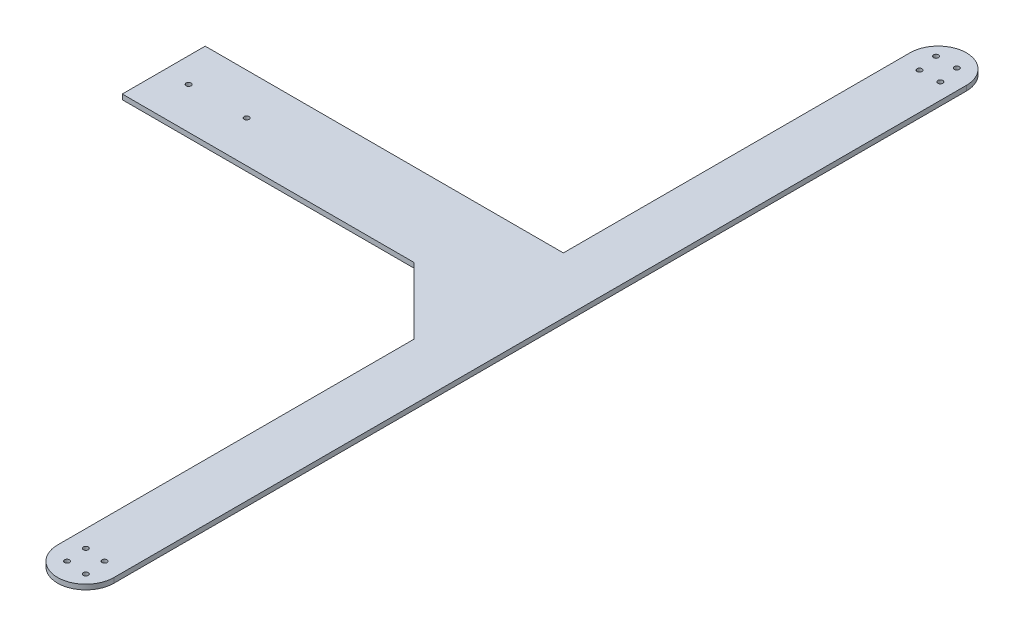
SolidWorks part; units mm, degrees
ref_plane "Front Plane" through (0, 0, 0) normal (0, 0, 1) x (1, 0, 0)
ref_plane "Top Plane" through (0, 0, 0) normal (0, 1, 0) x (1, 0, 0)
ref_plane "Right Plane" through (0, 0, 0) normal (1, 0, 0) x (0, 0, -1)
sketch "Sketch1" plane through (0, 0, 0) normal (0, 1, 0) x (1, 0, 0)
  line L0 (0, 0) -> (176, 0)
  line L1 (216, -40) -> (216, -255)
  line L2 (0, 0) -> (0, 50)
  line L3 (0, 50) -> (216, 50)
  line L4 (216, 50) -> (216, 259.0603)
  line L5 (250, -255) -> (250, 259.0603)
  line L6 (50, -120) -> (250, -120) construction
  line L7 (50, 150) -> (50, -120) construction
  line L8 (50, 150) -> (250, 120) construction
  line L9 (176, 0) -> (216, -40)
  line L10 (227.9078, 252.8902) -> (238.0922, 265.2304) construction
  line L11 (240.327, 253.0134) -> (225.673, 265.1073) construction
  line L12 (227.3431, -260.6569) -> (238.6569, -249.3431) construction
  line L13 (0, 25) -> (250, 25) construction
  line L14 (226.2825, -248.2825) -> (239.7175, -261.7175) construction
  arc A0 (216, -255) -> (250, -255) centre (233, -255) ccw
  arc A1 (216, 259.0603) -> (250, 259.0603) centre (233, 259.0603) cw
  circle A2 centre (233, -255) radius 135 construction
  circle A3 centre (233, 259.0603) radius 135 construction
  circle A4 centre (238.0922, 265.2304) radius 1.5
  circle A5 centre (225.673, 265.1073) radius 1.5
  circle A6 centre (227.9078, 252.8902) radius 1.5
  circle A7 centre (240.327, 253.0134) radius 1.5
  circle A8 centre (226.2825, -248.2825) radius 1.5
  circle A9 centre (238.6569, -249.3431) radius 1.5
  circle A10 centre (239.7175, -261.7175) radius 1.5
  circle A11 centre (227.3431, -260.6569) radius 1.5
  circle A12 centre (15, 25) radius 1.5
  circle A13 centre (50, 25) radius 1.5
  point P1 (216, 0)
  point P12 (250, 120)
  point P13 (250, -120)
  point P14 (50, 150)
  point P15 (50, -120)
  dimension "D1" = 17
  dimension "D3" = 270
  dimension "D4" = 270
  dimension "D12" = 3
  dimension "D13" = 3
  dimension "D14" = 3
  dimension "D15" = 3
  dimension "D20" = 3
  dimension "D21" = 3
  dimension "D22" = 3
  dimension "D23" = 3
  dimension "D24" = 3
  dimension "D25" = 3
  dimension "D27" = 50
  dimension "D2" = 50
  dimension "D5" = 240
  dimension "D6" = 200
  dimension "D7" = 50
  dimension "D8" = 120
  dimension "D9" = 16
  dimension "D10" = 19
  dimension "D16" = 270
  dimension "D17" = 45
  dimension "D18" = 16
  dimension "D19" = 19
  dimension "D26" = 15
extrude "Boss-Extrude1" add sketch "Sketch1" along normal blind 3 contours L1 A0 L5 L8 L4 L3 L7 L0 L9 A11 A10 A9 A8 | L7 L3 L2 L0 | A1 L4 L8 L5 A7 A6 A5 A4
